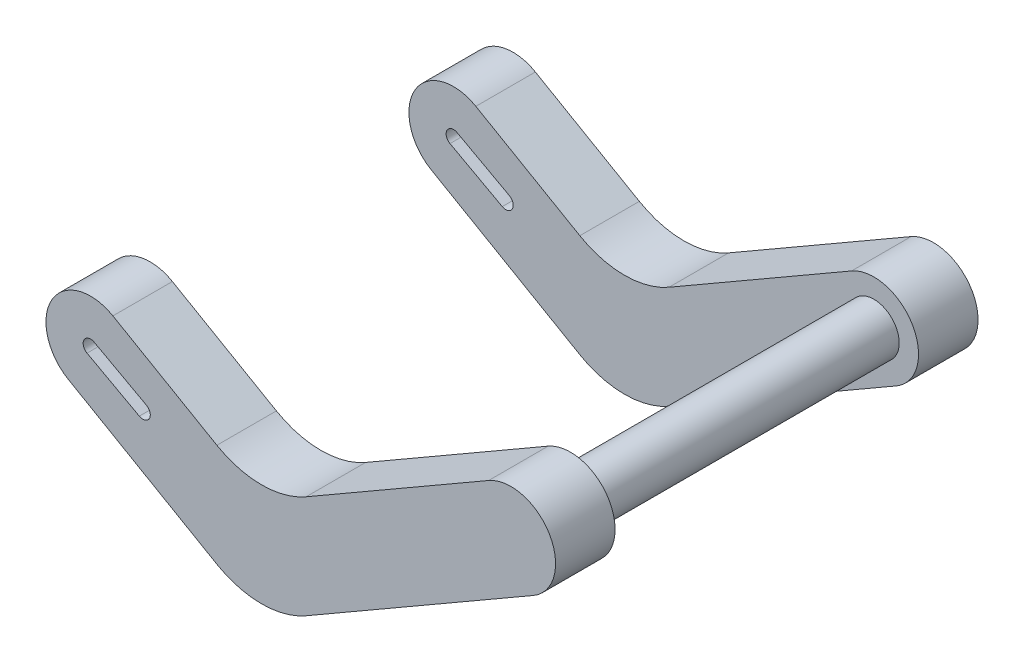
SolidWorks part; units mm, degrees
ref_plane "Front Plane" through (0, 0, 0) normal (0, 0, 1) x (1, 0, 0)
ref_plane "Top Plane" through (0, 0, 0) normal (0, 1, 0) x (1, 0, 0)
ref_plane "Right Plane" through (0, 0, 0) normal (1, 0, 0) x (0, 0, -1)
sketch "Sketch1" plane through (0, 0, 0) normal (0, 0, 1) x (1, 0, 0)
  line L0 (-7.76, 4.2216) -> (0, 0) construction
  line L1 (-7.01, 5.5207) -> (-2.0147, 2.6366)
  line L2 (-8.51, 2.9226) -> (-3.5147, 0.0385)
  line L3 (-7.76, 4.2216) -> (-6.0032, 3.2659) construction
  line L4 (-2.0147, 2.6366) -> (5.62, 7.0445)
  line L5 (-0.5147, 0.0385) -> (7.12, 4.4464)
  line L6 (-7.6405, 4.4412) -> (-5.8837, 3.4855)
  line L7 (-7.8795, 4.002) -> (-6.1226, 3.0463)
  arc A0 (-7.01, 5.5207) -> (-8.51, 2.9226) centre (-7.76, 4.2216) ccw
  arc A5 (5.62, 7.0445) -> (7.12, 4.4464) centre (6.37, 5.7455) cw
  arc A6 (-3.5147, 0.0385) -> (-0.5147, 0.0385) centre (-2.0147, 2.6366) ccw
  arc A7 (-7.6405, 4.4412) -> (-7.8795, 4.002) centre (-7.76, 4.2216) ccw
  arc A8 (-6.1226, 3.0463) -> (-5.8837, 3.4855) centre (-6.0032, 3.2659) ccw
  point P3 (-3.8106, 0.5803)
  point P9 (-6.8816, 3.7438)
  point P10 (3.3116, 2.3112)
  point P13 (-2.0147, -0.3634)
  dimension "D1" = 0.5
  dimension "D5" = 3
  dimension "D2" = 7.76
  dimension "D3" = 14.13
  dimension "D4" = 120
  dimension "D6" = 3
  dimension "D7" = 3
  dimension "D8" = 2
extrude "Boss-Extrude1" add sketch "Sketch1" along normal blind 2
sketch "Sketch2" plane through (0, 0, 2) normal (0, 0, 1) x (1, 0, 0)
  circle A3 centre (6.37, 5.7455) radius 0.85
  arc A4 (7.12, 4.4464) -> (5.62, 7.0445) centre (6.37, 5.7455) ccw construction
  dimension "D1" = 1.7
extrude "Boss-Extrude2" add sketch "Sketch2" along normal blind 10.2
ref_plane "Plane1" through (0, 0, 7.1) normal (0, 0, 1) x (1, 0, 0)
mirror "Mirror1" about plane through (0, 0, 7.1) normal (0, 0, 1) of "Boss-Extrude1"
fillet "Fillet1" radius 3 2 edges at (-2.0147, 2.6366, 13.2) (-2.0147, 2.6366, 1)
